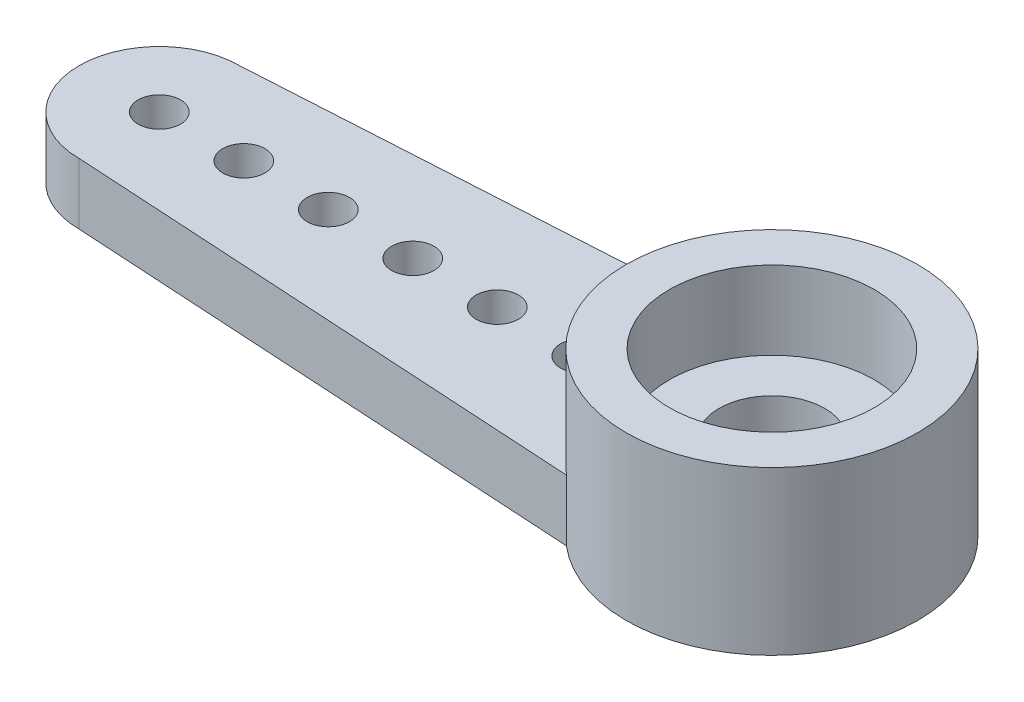
SolidWorks part; units mm, degrees
material "Q235"
ref_plane "前视" through (0, 0, 0) normal (0, 0, 1) x (1, 0, 0)
ref_plane "上视" through (0, 0, 0) normal (0, 1, 0) x (1, 0, 0)
ref_plane "右视" through (0, 0, 0) normal (1, 0, 0) x (0, 0, -1)
sketch "草图1" plane through (0, 0, 0) normal (0, 1, 0) x (1, 0, 0)
  circle A0 centre (0, 0) radius 3.45
  circle A1 centre (0, 0) radius 2.425
  dimension "D1" = 6.9
  dimension "D2" = 4.85
extrude "凸台-拉伸1" add sketch "草图1" along normal blind 3.85
ref_plane "基准面1" through (0, 1, 0) normal (0, -1, 0) x (-1, 0, 0)
sketch "草图2" plane through (0, 1, 0) normal (0, -1, 0) x (-1, 0, 0)
  circle A0 centre (0, 0) radius 1.25
  circle A1 centre (0, 0) radius 2.425 construction
  circle A2 centre (0, 0) radius 2.425
  dimension "D1" = 2.5
extrude "凸台-拉伸2" add sketch "草图2" against normal blind 1
sketch "草图3" plane through (0, 0, 0) normal (0, -1, 0) x (1, 0, 0)
  line L0 (0, 0) -> (-14.5779, 0) construction
  line L1 (-14.5, -1.9) -> (-2.2387, -2.625)
  line L2 (-14.5, 1.9) -> (-2.2387, 2.625)
  arc A0 (-14.5, 1.9) -> (-14.5, -1.9) centre (-14.5, 0) ccw
  circle A1 centre (-14.5, 0) radius 0.5
  circle A2 centre (0, 0) radius 3.45 construction
  arc A3 (-2.2387, 2.625) -> (-2.2387, -2.625) centre (0, 0) ccw
  circle A4 centre (-12.5, 0) radius 0.5
  circle A5 centre (-10.5, 0) radius 0.5
  circle A6 centre (-8.5, 0) radius 0.5
  circle A7 centre (-6.5, 0) radius 0.5
  circle A8 centre (-4.5, 0) radius 0.5
  dimension "D1" = 3.8
  dimension "D2" = 1
  dimension "D3" = 14.5
  dimension "D4" = 5.25
  dimension "D6" = 12.2613
  dimension "D7" = 0.725
  dimension "D5" = 6
extrude "凸台-拉伸3" add sketch "草图3" against normal blind 1.45
sketch "草图4" plane through (0, 0, 0) normal (0, -1, 0) x (1, 0, 0)
  line L0 (-2.2387, -2.625) -> (-2.2387, 2.625)
  dimension "D1" = 5.25
